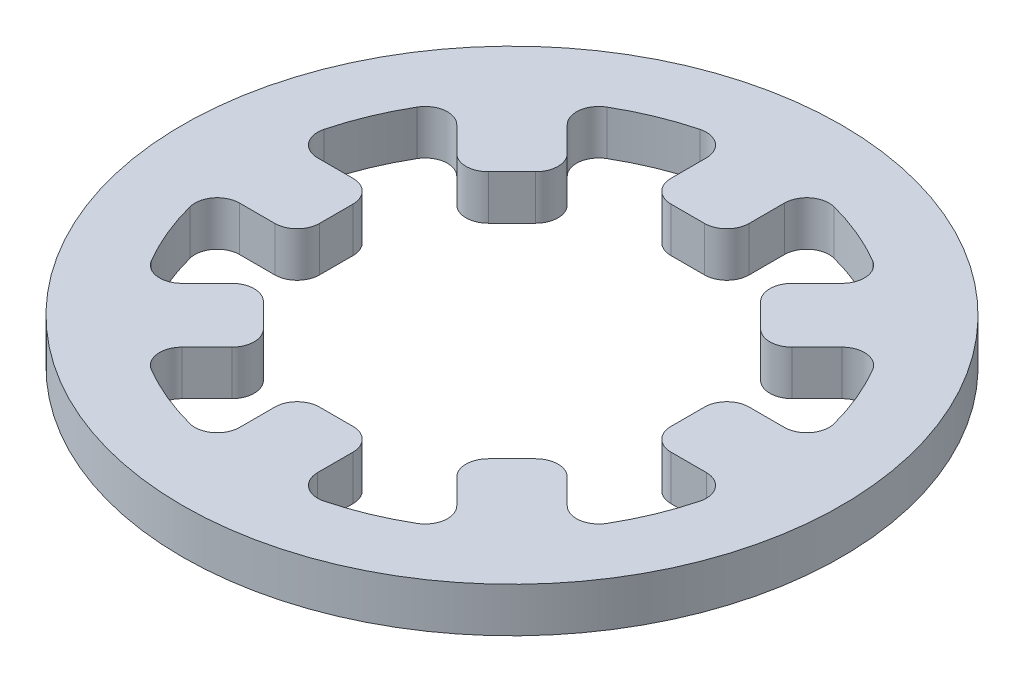
SolidWorks part; units mm, degrees
material "Plain Carbon Steel"
ref_plane "Front Plane" through (0, 0, 0) normal (0, 0, 1) x (1, 0, 0)
ref_plane "Top Plane" through (0, 0, 0) normal (0, 1, 0) x (1, 0, 0)
ref_plane "Right Plane" through (0, 0, 0) normal (1, 0, 0) x (0, 0, -1)
sketch "Sketch1" plane through (0, 0, 0) normal (0, 1, 0) x (1, 0, 0)
  line L0 (-0.889, 5.3114) -> (-0.889, 4.508)
  line L1 (-0.381, 4) -> (0.381, 4)
  line L2 (0.889, 4.508) -> (0.889, 5.3114)
  line L3 (3.1271, 4.3843) -> (2.559, 3.8163)
  line L4 (3.8163, 2.559) -> (4.3843, 3.1271)
  line L5 (2.559, 3.0978) -> (3.0978, 2.559)
  line L6 (5.3114, 0.889) -> (4.508, 0.889)
  line L7 (4.508, -0.889) -> (5.3114, -0.889)
  line L8 (4, 0.381) -> (4, -0.381)
  line L9 (4.3843, -3.1271) -> (3.8163, -2.559)
  line L10 (2.559, -3.8163) -> (3.1271, -4.3843)
  line L11 (3.0978, -2.559) -> (2.559, -3.0978)
  line L12 (0.889, -5.3114) -> (0.889, -4.508)
  line L13 (-0.889, -4.508) -> (-0.889, -5.3114)
  line L14 (0.381, -4) -> (-0.381, -4)
  line L15 (-3.1271, -4.3843) -> (-2.559, -3.8163)
  line L16 (-3.8163, -2.559) -> (-4.3843, -3.1271)
  line L17 (-2.559, -3.0978) -> (-3.0978, -2.559)
  line L18 (-5.3114, -0.889) -> (-4.508, -0.889)
  line L19 (-4.508, 0.889) -> (-5.3114, 0.889)
  line L20 (-4, -0.381) -> (-4, 0.381)
  line L21 (-4.3843, 3.1271) -> (-3.8163, 2.559)
  line L22 (-2.559, 3.8163) -> (-3.1271, 4.3843)
  line L23 (-3.0978, 2.559) -> (-2.559, 3.0978)
  circle A0 centre (0, 0) radius 7.5
  arc A1 (-1.5262, 5.8026) -> (-3.0239, 5.1823) centre (0, 0) ccw
  arc A2 (-5.1823, 3.0239) -> (-5.8026, 1.5262) centre (0, 0) ccw
  arc A3 (-5.8026, -1.5262) -> (-5.1823, -3.0239) centre (0, 0) ccw
  arc A4 (-3.0239, -5.1823) -> (-1.5262, -5.8026) centre (0, 0) ccw
  arc A5 (1.5262, -5.8026) -> (3.0239, -5.1823) centre (0, 0) ccw
  arc A6 (5.1823, -3.0239) -> (5.8026, -1.5262) centre (0, 0) ccw
  arc A7 (5.8026, 1.5262) -> (5.1823, 3.0239) centre (0, 0) ccw
  arc A8 (3.0239, 5.1823) -> (1.5262, 5.8026) centre (0, 0) ccw
  arc A9 (-3.1271, 4.3843) -> (-3.0239, 5.1823) centre (-2.7679, 4.7435) cw
  arc A10 (-2.559, 3.8163) -> (-2.559, 3.0978) centre (-2.9182, 3.457) cw
  arc A11 (-3.8163, 2.559) -> (-3.0978, 2.559) centre (-3.457, 2.9182) ccw
  arc A12 (-4.3843, 3.1271) -> (-5.1823, 3.0239) centre (-4.7435, 2.7679) ccw
  arc A13 (-5.3114, 0.889) -> (-5.8026, 1.5262) centre (-5.3114, 1.397) cw
  arc A14 (-4.508, 0.889) -> (-4, 0.381) centre (-4.508, 0.381) cw
  arc A15 (-4.508, -0.889) -> (-4, -0.381) centre (-4.508, -0.381) ccw
  arc A16 (-5.3114, -0.889) -> (-5.8026, -1.5262) centre (-5.3114, -1.397) ccw
  arc A17 (-4.3843, -3.1271) -> (-5.1823, -3.0239) centre (-4.7435, -2.7679) cw
  arc A18 (-3.8163, -2.559) -> (-3.0978, -2.559) centre (-3.457, -2.9182) cw
  arc A19 (-2.559, -3.8163) -> (-2.559, -3.0978) centre (-2.9182, -3.457) ccw
  arc A20 (-3.1271, -4.3843) -> (-3.0239, -5.1823) centre (-2.7679, -4.7435) ccw
  arc A21 (-0.889, -5.3114) -> (-1.5262, -5.8026) centre (-1.397, -5.3114) cw
  arc A22 (-0.889, -4.508) -> (-0.381, -4) centre (-0.381, -4.508) cw
  arc A23 (0.889, -4.508) -> (0.381, -4) centre (0.381, -4.508) ccw
  arc A24 (0.889, -5.3114) -> (1.5262, -5.8026) centre (1.397, -5.3114) ccw
  arc A25 (3.1271, -4.3843) -> (3.0239, -5.1823) centre (2.7679, -4.7435) cw
  arc A26 (2.559, -3.8163) -> (2.559, -3.0978) centre (2.9182, -3.457) cw
  arc A27 (3.8163, -2.559) -> (3.0978, -2.559) centre (3.457, -2.9182) ccw
  arc A28 (4.3843, -3.1271) -> (5.1823, -3.0239) centre (4.7435, -2.7679) ccw
  arc A29 (5.3114, -0.889) -> (5.8026, -1.5262) centre (5.3114, -1.397) cw
  arc A30 (4.508, -0.889) -> (4, -0.381) centre (4.508, -0.381) cw
  arc A31 (4.508, 0.889) -> (4, 0.381) centre (4.508, 0.381) ccw
  arc A32 (5.3114, 0.889) -> (5.8026, 1.5262) centre (5.3114, 1.397) ccw
  arc A33 (4.3843, 3.1271) -> (5.1823, 3.0239) centre (4.7435, 2.7679) cw
  arc A34 (3.8163, 2.559) -> (3.0978, 2.559) centre (3.457, 2.9182) cw
  arc A35 (2.559, 3.8163) -> (2.559, 3.0978) centre (2.9182, 3.457) ccw
  arc A36 (3.1271, 4.3843) -> (3.0239, 5.1823) centre (2.7679, 4.7435) ccw
  arc A37 (0.889, 5.3114) -> (1.5262, 5.8026) centre (1.397, 5.3114) cw
  arc A38 (0.381, 4) -> (0.889, 4.508) centre (0.381, 4.508) ccw
  arc A39 (-0.889, 4.508) -> (-0.381, 4) centre (-0.381, 4.508) ccw
  arc A40 (-0.889, 5.3114) -> (-1.5262, 5.8026) centre (-1.397, 5.3114) ccw
  point P39 (0, 0)
  point P98 (0.889, 4)
  point P101 (-0.889, 4)
  dimension "D1" = 15
  dimension "D2" = 12
  dimension "D6" = 0.508
  dimension "D3" = 4
  dimension "D4" = 1.778
  dimension "D5" = 8
extrude "Boss-Extrude1" add sketch "Sketch1" along normal blind 1.016
